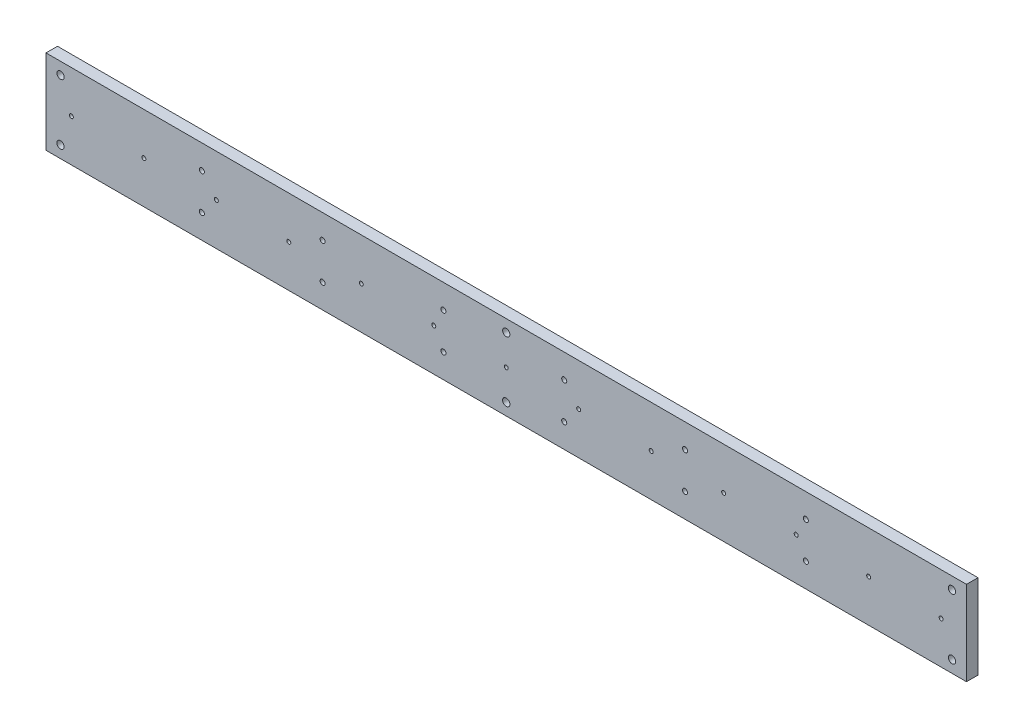
SolidWorks part; units mm, degrees
ref_plane "Front Plane" through (0, 0, 0) normal (0, 0, 1) x (1, 0, 0)
ref_plane "Top Plane" through (0, 0, 0) normal (0, 1, 0) x (1, 0, 0)
ref_plane "Right Plane" through (0, 0, 0) normal (1, 0, 0) x (0, 0, -1)
sketch "Sketch1" plane through (0, 0, 0) normal (0, 0, 1) x (1, 0, 0)
  line L1 (0, 0) -> (762, 0)
  line L2 (0, 0) -> (0, 69.85)
  line L3 (0, 69.85) -> (762, 69.85)
  line L4 (762, 0) -> (762, 69.85)
  dimension "D1" = 69.85
  dimension "D2" = 762
extrude "Boss-Extrude1" add sketch "Sketch1" along normal blind 9.525
sketch "Sketch2" plane through (0, 0, 0) normal (0, 0, -1) x (-1, 0, 0)
  line L0 (-762, 0) -> (-762, 69.85) construction
  line L1 (-762, 69.85) -> (0, 69.85) construction
  line L3 (0, 69.85) -> (0, 0) construction
  circle A0 centre (-750, 59.925) radius 6
  circle A1 centre (-750, 9.925) radius 6
  circle A2 centre (-381, 9.925) radius 6
  circle A3 centre (-381, 59.925) radius 6
  circle A4 centre (-12, 59.925) radius 6
  circle A5 centre (-12, 9.925) radius 6
  circle A6 centre (-750, 59.925) radius 3
  circle A7 centre (-750, 9.925) radius 3
  circle A8 centre (-12, 59.925) radius 3
  circle A9 centre (-12, 9.925) radius 3
  circle A10 centre (-381, 59.925) radius 3
  circle A11 centre (-381, 9.925) radius 3
  dimension "D4" = 12
  dimension "D5" = 6
  dimension "D6" = 12
  dimension "D7" = 6
  dimension "D9" = 12
  dimension "D10" = 12
  dimension "D11" = 6
  dimension "D12" = 6
  dimension "D14" = 12
  dimension "D15" = 12
  dimension "D16" = 6
  dimension "D17" = 6
  dimension "D1" = 50
  dimension "D2" = 12
  dimension "D3" = 9.925
  dimension "D8" = 12
  dimension "D13" = 369
hole_wizard "Hole1" positions "3DSketch1" profile "Sketch3" legacy end condition through all
sketch3d "3DSketch1"
  point P0 (750, 59.925, 0)
  point P3 (750, 9.925, 0)
  point P6 (381, 59.925, 0)
  point P9 (381, 9.925, 0)
  point P12 (12, 59.925, 0)
  point P15 (12, 9.925, 0)
sketch "Sketch3" plane through (750, 59.925, 0) normal (1, 0, 0) x (0, 1, 0)
  line L0 (0, 0) -> (0, 9.525)
  line L1 (0, 9.525) -> (3, 9.525)
  line L3 (3, 9.525) -> (3, 4.1)
  line L4 (3, 4.1) -> (6, 4.1)
  line L5 (6, 4.1) -> (6, 0)
  line L7 (6, 0) -> (0, 0)
  line L11 (0, -6.35) -> (0, 107.95) construction
  dimension "Thru Hole Dia." = 6
  dimension "Thru Hole Depth" = 9.525
  dimension "C'Bore Dia." = 12
  dimension "C'Bore Depth" = 4.1
sketch "Sketch4" plane through (0, 0, 0) normal (0, 0, -1) x (-1, 0, 0)
  line L0 (-762, 0) -> (-762, 69.85) construction
  line L1 (-762, 69.85) -> (0, 69.85) construction
  point P0 (-681, 34.925)
  point P1 (-741, 34.925)
  point P2 (-621, 34.925)
  point P3 (-561, 34.925)
  point P4 (-501, 34.925)
  point P5 (-441, 34.925)
  point P6 (-381, 34.925)
  point P7 (-321, 34.925)
  point P8 (-261, 34.925)
  point P9 (-201, 34.925)
  point P10 (-141, 34.925)
  point P11 (-81, 34.925)
  point P12 (-21, 34.925)
  dimension "D1" = 120
  dimension "D2" = 60
  dimension "D3" = 60
  dimension "D4" = 60
  dimension "D5" = 60
  dimension "D6" = 60
  dimension "D7" = 60
  dimension "D8" = 60
  dimension "D9" = 60
  dimension "D10" = 60
  dimension "D11" = 60
  dimension "D12" = 60
  dimension "D13" = 21
  dimension "D14" = 34.925
hole_wizard "M4x0.7 Tapped Hole1" positions "3DSketch2" profile "Sketch5" tap size "M4x0.7" standard "Ansi Metric"
sketch3d "3DSketch2"
  point P0 (741, 34.925, 0)
  point P3 (681, 34.925, 0)
  point P6 (621, 34.925, 0)
  point P9 (561, 34.925, 0)
  point P12 (501, 34.925, 0)
  point P15 (441, 34.925, 0)
  point P18 (381, 34.925, 0)
  point P21 (321, 34.925, 0)
  point P24 (261, 34.925, 0)
  point P27 (201, 34.925, 0)
  point P30 (141, 34.925, 0)
  point P33 (81, 34.925, 0)
  point P36 (21, 34.925, 0)
sketch "Sketch5" plane through (741, 34.925, 0) normal (1, 0, 0) x (0, 1, 0)
  line L0 (0, 0) -> (0, 11.0914)
  line L1 (0, 11.0914) -> (1.65, 10.1)
  line L2 (1.65, 10.1) -> (1.65, 0)
  line L5 (1.65, 0) -> (0, 0)
  line L10 (0, 11.0914) -> (-1.65, 10.1) construction
  line L11 (0, -6.35) -> (0, 107.95) construction
  dimension "Tap Drill Dia." = 3.3
  dimension "Tap Drill Depth" = 10.1
  dimension "Drill Angle" = 118
cosmetic thread "Hole Thread1"
cosmetic thread "Hole Thread2"
cosmetic thread "Hole Thread3"
cosmetic thread "Hole Thread4"
cosmetic thread "Hole Thread5"
cosmetic thread "Hole Thread6"
cosmetic thread "Hole Thread7"
cosmetic thread "Hole Thread8"
cosmetic thread "Hole Thread9"
cosmetic thread "Hole Thread10"
cosmetic thread "Hole Thread11"
cosmetic thread "Hole Thread12"
cosmetic thread "Hole Thread13"
sketch "Sketch7" plane through (0, 0, 0) normal (0, 0, -1) x (-1, 0, 0)
  circle A0 centre (-629, 19.925) radius 2.75
  circle A1 centre (-629, 49.925) radius 2.75
  circle A2 centre (-529, 49.925) radius 2.75
  circle A3 centre (-529, 19.925) radius 2.75
  circle A4 centre (-429, 49.925) radius 2.75
  circle A5 centre (-429, 19.925) radius 2.75
  circle A6 centre (-329, 49.925) radius 2.75
  circle A7 centre (-329, 19.925) radius 2.75
  circle A8 centre (-229, 49.925) radius 2.75
  circle A9 centre (-229, 19.925) radius 2.75
  circle A10 centre (-129, 49.925) radius 2.75
  circle A11 centre (-129, 19.925) radius 2.75
  point P24 (-21, 34.925)
  point P25 (-741, 34.925)
hole_wizard "M5x0.8 Tapped Hole1" positions "3DSketch3" profile "Sketch8" tap size "M5x0.8" standard "Ansi Metric"
sketch3d "3DSketch3"
  point P0 (629, 49.925, 0)
  point P3 (629, 19.925, 0)
  point P6 (529, 49.925, 0)
  point P9 (529, 19.925, 0)
  point P12 (429, 49.925, 0)
  point P15 (429, 19.925, 0)
  point P18 (329, 49.925, 0)
  point P21 (329, 19.925, 0)
  point P24 (229, 49.925, 0)
  point P27 (229, 19.925, 0)
  point P30 (129, 49.925, 0)
  point P33 (129, 19.925, 0)
sketch "Sketch8" plane through (629, 49.925, 0) normal (1, 0, 0) x (0, 1, 0)
  line L0 (0, 0) -> (0, 13.6618)
  line L1 (0, 13.6618) -> (2.1, 12.4)
  line L2 (2.1, 12.4) -> (2.1, 0)
  line L5 (2.1, 0) -> (0, 0)
  line L10 (0, 13.6618) -> (-2.1, 12.4) construction
  line L11 (0, -6.35) -> (0, 107.95) construction
  dimension "Tap Drill Dia." = 4.2
  dimension "Tap Drill Depth" = 12.4
  dimension "Drill Angle" = 118
cosmetic thread "Hole Thread14"
cosmetic thread "Hole Thread15"
cosmetic thread "Hole Thread16"
cosmetic thread "Hole Thread17"
cosmetic thread "Hole Thread18"
cosmetic thread "Hole Thread19"
cosmetic thread "Hole Thread20"
cosmetic thread "Hole Thread21"
cosmetic thread "Hole Thread22"
cosmetic thread "Hole Thread23"
cosmetic thread "Hole Thread24"
cosmetic thread "Hole Thread25"
